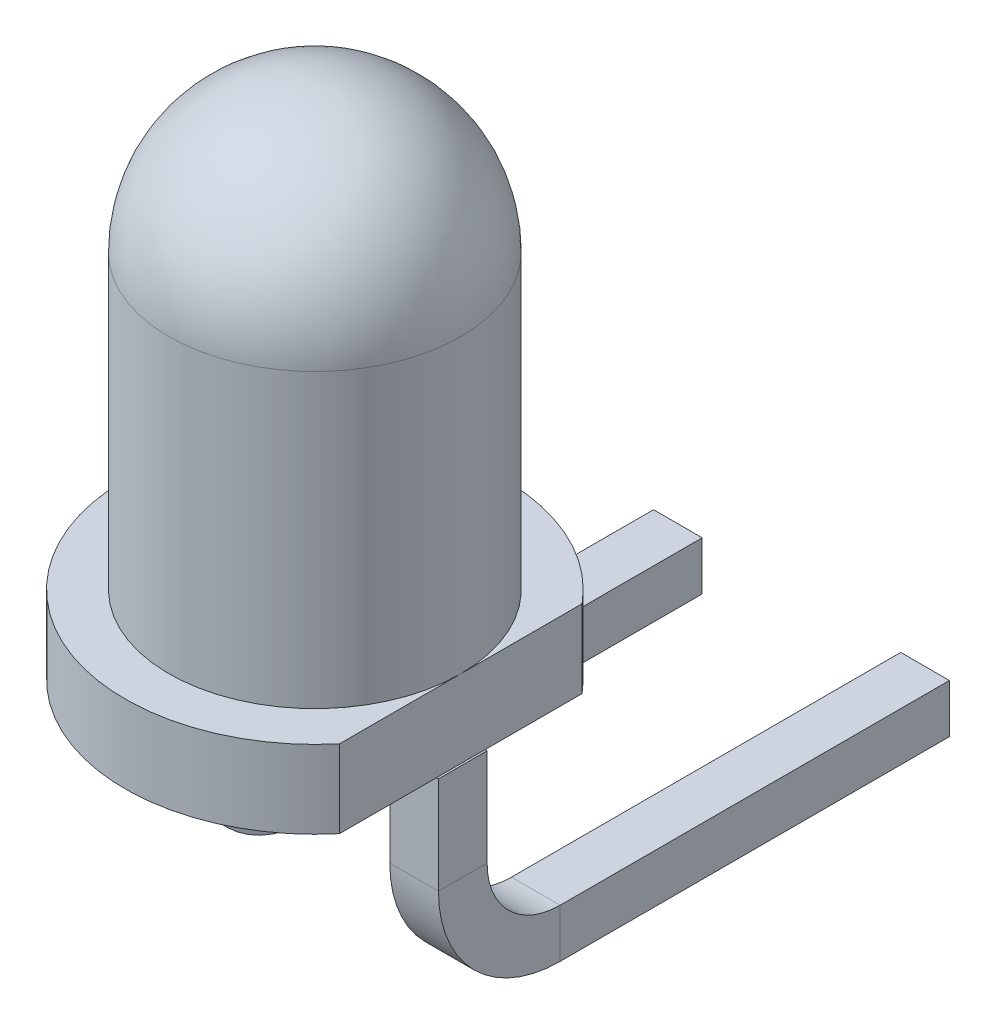
SolidWorks part; units mm, degrees
ref_plane "Front Plane" through (0, 0, 0) normal (0, 0, 1) x (1, 0, 0)
ref_plane "Top Plane" through (0, 0, 0) normal (0, 1, 0) x (1, 0, 0)
ref_plane "Right Plane" through (0, 0, 0) normal (1, 0, 0) x (0, 0, -1)
sketch "Sketch1" plane through (0, 0, 0) normal (0, 0, -1) x (1, 0, 0)
  line L0 (0, 0) -> (0, -5.3)
  line L1 (1.5, -3.8) -> (1.5, -0.8)
  line L2 (1.95, 0) -> (0, 0)
  line L3 (1.5, -0.8) -> (1.95, -0.8)
  line L4 (1.95, -0.8) -> (1.95, 0)
  line L5 (0, 0) -> (0, -11.6681) construction
  arc A0 (1.5, -3.8) -> (0, -5.3) centre (0, -3.8) cw
  dimension "D1" = 3
  dimension "D2" = 3.9
  dimension "D3" = 0.8
  dimension "D4" = 4.5
revolve "Revolve1" add sketch "Sketch1" angle 360 about L0
sketch "Sketch2" plane through (0, 0, 0) normal (0, -1, 0) x (-1, 0, 0)
  line L0 (-1.95, -1.246) -> (-1.95, 1.246)
  line L1 (-1.95, 1.246) -> (-1.5, 1.246)
  line L3 (-1.95, -1.246) -> (-1.5, -1.246)
  line L4 (-1.5, 1.246) -> (-1.5, -1.246)
  circle A1 centre (0, 0) radius 1.95 construction
  circle A2 centre (0, 0) radius 1.95 construction
  circle A3 centre (0, 0) radius 1.5 construction
extrude "Cut-Extrude1" cut sketch "Sketch2" against normal through all
sketch "Sketch3" plane through (0, 0, 0) normal (0, -1, 0) x (-1, 0, 0)
  line L0 (0, 1.7562) -> (0, 0) construction
  line L1 (0, 0) -> (1.27, 0) construction
  line L2 (-1.02, 0.25) -> (-1.02, -0.25)
  line L3 (1.02, 0.25) -> (1.52, 0.25)
  line L4 (1.02, 0.25) -> (1.02, -0.25)
  line L5 (1.02, -0.25) -> (1.52, -0.25)
  line L6 (1.52, 0.25) -> (1.52, -0.25)
  line L7 (1.02, 0.25) -> (1.52, -0.25) construction
  line L8 (1.02, -0.25) -> (1.52, 0.25) construction
  line L9 (-1.02, -0.25) -> (-1.52, -0.25)
  line L10 (-1.52, 0.25) -> (-1.52, -0.25)
  line L11 (-1.02, 0.25) -> (-1.52, 0.25)
  dimension "D1" = 0.5
  dimension "D2" = 1.27
ref_plane "Plane1" through (-1.27, 0, 0) normal (1, 0, 0) x (0, 0, -1)
sketch "Sketch4" plane through (-1.27, 0, 0) normal (1, 0, 0) x (0, 0, -1)
  line L0 (0, 0) -> (0, -1)
  line L1 (1, -2) -> (5, -2)
  line L2 (1.7562, 0) -> (0, 0) construction
  arc A0 (0, -1) -> (1, -2) centre (1, -1) ccw
  dimension "D3" = 5
  dimension "D2" = 1
  dimension "D1" = 2
sweep "Sweep1" add profiles "Sketch3" path "Sketch4"
